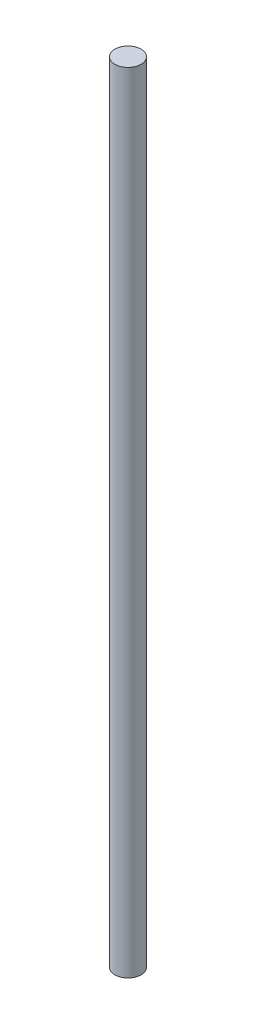
SolidWorks part; units mm, degrees
ref_plane "Front Plane" through (0, 0, 0) normal (0, 0, 1) x (1, 0, 0)
ref_plane "Top Plane" through (0, 0, 0) normal (0, 1, 0) x (1, 0, 0)
ref_plane "Right Plane" through (0, 0, 0) normal (1, 0, 0) x (0, 0, -1)
sketch "Sketch1" plane through (0, 0, 0) normal (0, 1, 0) x (1, 0, 0)
  circle A0 centre (0, 0) radius 6
  dimension "D1" = 12
extrude "Boss-Extrude1" add sketch "Sketch1" along normal blind 361
equation "\"d\"= 12"
equation "\"l\"=361"
equation "\"D1@Boss-Extrude1\"=\"l\""
equation "\"D1@Sketch1\"=\"d\""
